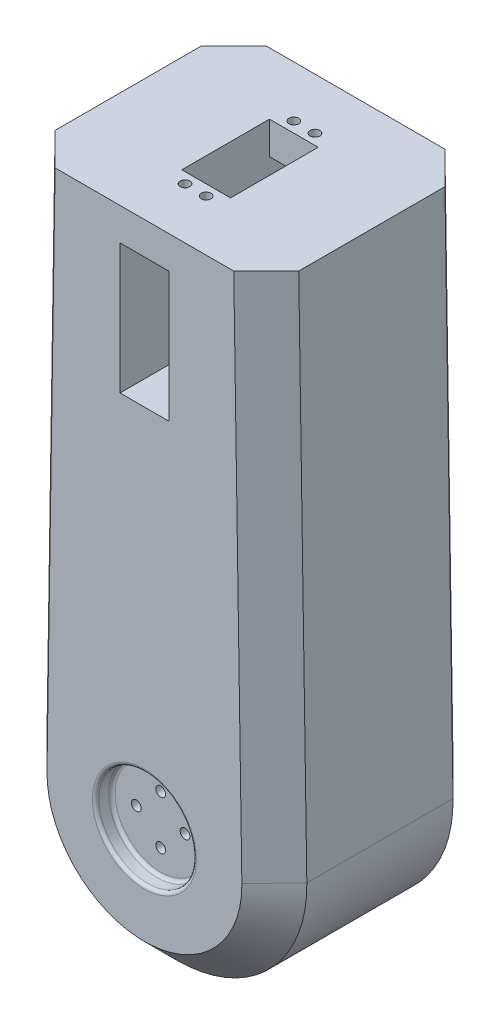
SolidWorks part; units mm, degrees
ref_plane "Front Plane" through (0, 0, 0) normal (0, 0, 1) x (1, 0, 0)
ref_plane "Top Plane" through (0, 0, 0) normal (0, 1, 0) x (1, 0, 0)
ref_plane "Right Plane" through (0, 0, 0) normal (1, 0, 0) x (0, 0, -1)
sketch "Sketch1" plane through (0, 0, 0) normal (0, 0, 1) x (1, 0, 0)
  line L0 (0, -1042.0579) -> (0, 51060.8348) construction
  line L1 (-37.5, 162.5) -> (37.5, 162.5)
  line L2 (37.5, 162.5) -> (39.9952, 0.6165)
  line L3 (-37.5, 162.5) -> (-39.9952, 0.6165)
  arc A0 (-39.9952, 0.6165) -> (39.9952, 0.6165) centre (0, 0) ccw
  point P8 (0, 162.5)
  dimension "D1" = 80
  dimension "D2" = 75
  dimension "D3" = 162.5
extrude "Boss-Extrude1" add sketch "Sketch1" along normal blind 65
chamfer "Chamfer1" distance 10 6 edges at (-38.7476, 81.5582, 0) (0, -40, 0) (38.7476, 81.5582, 0) (-38.7476, 81.5582, 65) (0, -40, 65) (38.7476, 81.5582, 65)
sketch "Sketch2" plane through (0, 0, 65) normal (0, 0, 1) x (1, 0, 0)
  circle A0 centre (0, 0) radius 15
  dimension "D1" = 30
extrude "Cut-Extrude1" cut sketch "Sketch2" against normal blind 5
sketch "Sketch3" plane through (0, 0, 60) normal (0, 0, 1) x (1, 0, 0)
  line L0 (0, 15) -> (0, -15) construction
  line L1 (-15, 0) -> (15, 0) construction
  circle A0 centre (0, 0) radius 15 construction
  circle A2 centre (0, 7.5) radius 1.5
  circle A3 centre (0, 0) radius 15 construction
  circle A4 centre (7.5, 0) radius 1.5
  circle A5 centre (0, -7.5) radius 1.5
  circle A6 centre (-7.5, 0) radius 1.5
  point P20 (0, 0)
  dimension "D1" = 3
  dimension "D2" = 7.5
  dimension "D3" = 4
extrude "Cut-Extrude2" cut sketch "Sketch3" against normal blind 7.5
fillet "Fillet1" radius 1 2 edges at (15, 0, 65) (15, 0, 60)
sketch "Sketch4" plane through (0, 0, 65) normal (0, 0, 1) x (1, 0, 0)
  line L0 (0, 162.5) -> (0, 58.6119) construction
  line L1 (27.4988, 162.5) -> (-27.4988, 162.5) construction
  line L3 (-7.5, 152.5) -> (7.5, 152.5)
  line L4 (-7.5, 152.5) -> (-7.5, 112.5)
  line L5 (-7.5, 112.5) -> (7.5, 112.5)
  line L6 (7.5, 152.5) -> (7.5, 112.5)
  line L7 (-7.5, 152.5) -> (7.5, 112.5) construction
  line L8 (-7.5, 112.5) -> (7.5, 152.5) construction
  point P5 (0, 132.5)
  dimension "D1" = 40
  dimension "D2" = 15
  dimension "D3" = 10
extrude "Cut-Extrude3" cut sketch "Sketch4" against normal through all
sketch "Sketch5" plane through (0, 162.5, 0) normal (0, 1, 0) x (1, 0, 0)
  line L0 (0, 0) -> (0, -65) construction
  line L1 (27.4988, -65) -> (-27.4988, -65) construction
  line L2 (-17.0953, -32.5) -> (22.6613, -32.5) construction
  line L3 (-7.5, -19) -> (7.5, -19)
  line L4 (-7.5, -19) -> (-7.5, -46)
  line L5 (-7.5, -46) -> (7.5, -46)
  line L6 (7.5, -19) -> (7.5, -46)
  line L7 (-7.5, -19) -> (7.5, -46) construction
  line L8 (-7.5, -46) -> (7.5, -19) construction
  circle A0 centre (-3.25, -15.75) radius 1.5
  circle A1 centre (3.25, -15.75) radius 1.5
  circle A2 centre (3.25, -49.25) radius 1.5
  circle A3 centre (-3.25, -49.25) radius 1.5
  point P5 (0, -32.5)
  dimension "D3" = 3
  dimension "D1" = 27
  dimension "D2" = 15
  dimension "D4" = 3.25
  dimension "3.25" = 3.25
extrude "Cut-Extrude4" cut sketch "Sketch5" against normal up to surface (10 mm away) up to face at (0, 152.5, 32.5)
sketch "Sketch6" plane through (0, 162.5, 0) normal (0, 1, 0) x (1, 0, 0)
  line L0 (0, -19) -> (0, -46) construction
  line L1 (7.5, -19) -> (-7.5, -19) construction
  line L2 (-7.5, -46) -> (7.5, -46) construction
  circle A0 centre (0, -32.5) radius 3.75 construction
  dimension "D1" = 7.5
